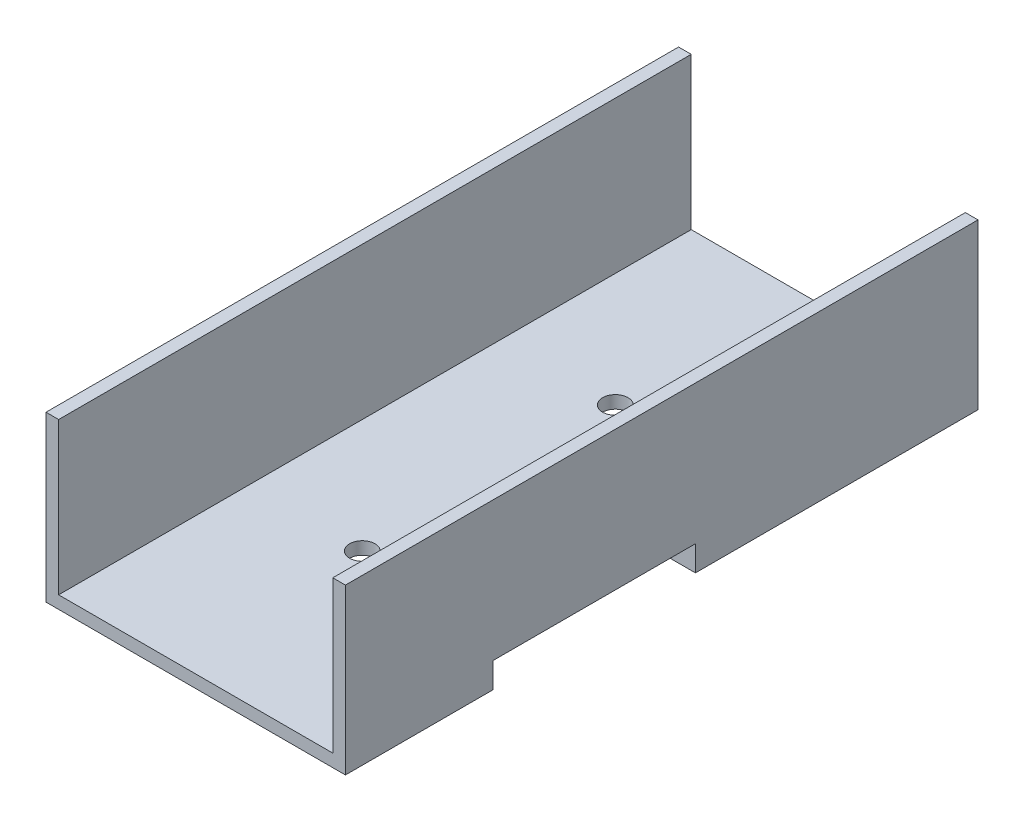
SolidWorks part; units mm, degrees
material "3.0205 (EN-AW 1200)"
ref_plane "Plan de face" through (0, 0, 0) normal (0, 0, 1) x (1, 0, 0)
ref_plane "Plan de dessus" through (0, 0, 0) normal (0, 1, 0) x (1, 0, 0)
ref_plane "Plan de droite" through (0, 0, 0) normal (1, 0, 0) x (0, 0, -1)
sketch "Esquisse1" plane through (0, 0, 0) normal (0, 0, 1) x (1, 0, 0)
  line L0 (-17.75, 19.5) -> (-17.75, 0)
  line L1 (-17.75, 0) -> (17.75, 0)
  line L2 (17.75, 0) -> (17.75, 19.5)
  dimension "D1" = 19.5
  dimension "D2" = 35.5
extrude "Extru.-Mince1" add sketch "Esquisse1" along normal mid plane 75 thin thin type one direction reverse wall 1.5
sketch "Esquisse2" plane through (0, 0, 0) normal (0, -1, 0) x (1, 0, 0)
  line L1 (11.75, 20) -> (17.75, 20)
  line L2 (7.75, 16) -> (7.75, 0)
  line L3 (11.75, -4) -> (17.75, -4)
  line L4 (17.75, 20) -> (17.75, -4)
  line L5 (17.75, 37.5) -> (17.75, -37.5) construction
  line L6 (10.725, 0) -> (-10.725, 0) construction
  line L7 (-17.75, 37.5) -> (-17.75, -37.5) construction
  arc A0 (7.75, 0) -> (11.75, -4) centre (11.75, 0) ccw
  arc A1 (11.75, 20) -> (7.75, 16) centre (11.75, 16) ccw
  circle A2 centre (-2.75, 15) radius 1.5
  circle A3 centre (-2.75, -15) radius 1.5
  point P14 (7.75, 20)
  dimension "D2" = 4
  dimension "D5" = 30
  dimension "D6" = 15
  dimension "D7" = 3
  dimension "D1" = 10
  dimension "D3" = 20
  dimension "D4" = 4
extrude "Enlèv. mat.-Extru.1" cut sketch "Esquisse2" against normal blind 3
